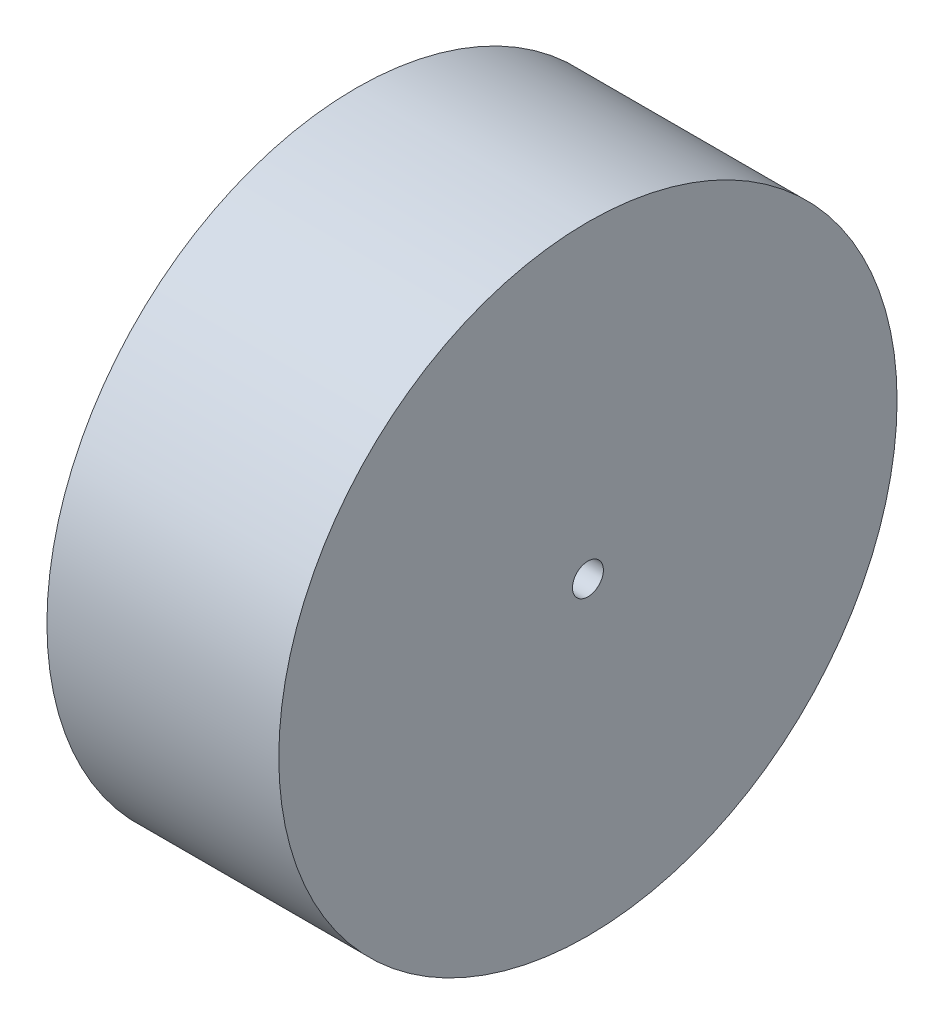
SolidWorks part; units mm, degrees
ref_plane "Front Plane" through (0, 0, 0) normal (0, 0, 1) x (1, 0, 0)
ref_plane "Top Plane" through (0, 0, 0) normal (0, 1, 0) x (1, 0, 0)
ref_plane "Right Plane" through (0, 0, 0) normal (1, 0, 0) x (0, 0, -1)
sketch "Sketch1" plane through (0, 0, 0) normal (1, 0, 0) x (0, 0, -1)
  circle A0 centre (0, 0) radius 1
  circle A1 centre (0, 0) radius 20
  dimension "D1" = 40
  dimension "D2" = 2
extrude "Boss-Extrude1" add sketch "Sketch1" along normal blind 15
